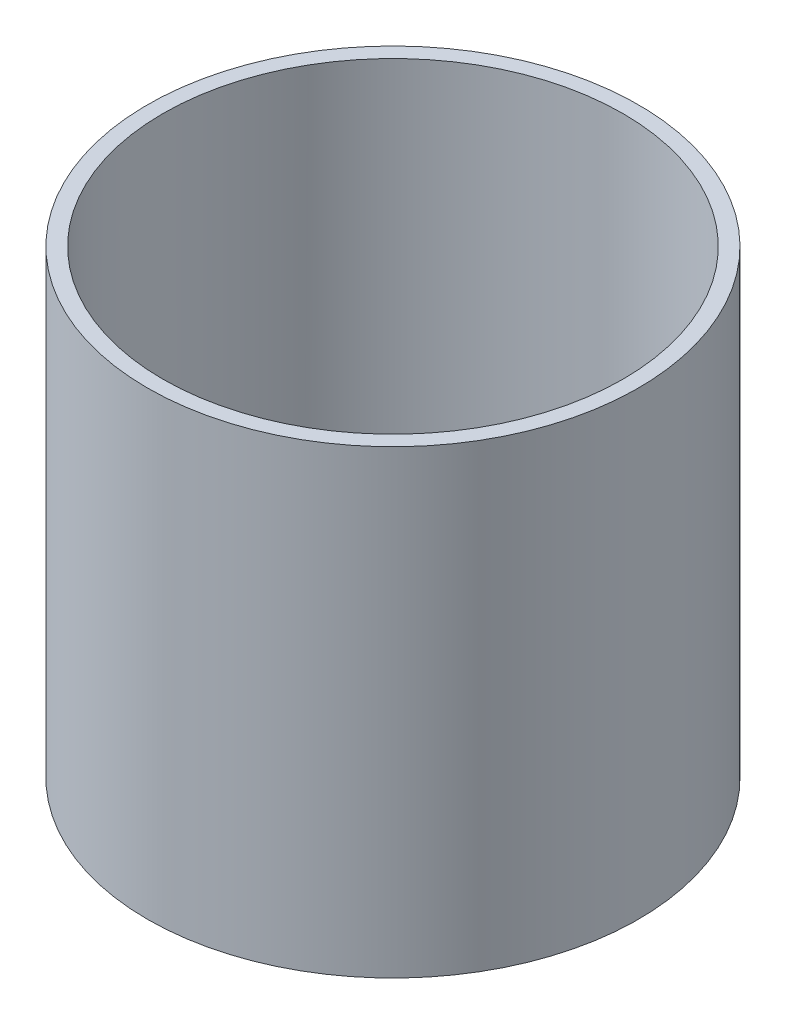
SolidWorks part; units mm, degrees
ref_plane "Plan de face" through (0, 0, 0) normal (0, 0, 1) x (1, 0, 0)
ref_plane "Plan de dessus" through (0, 0, 0) normal (0, 1, 0) x (1, 0, 0)
ref_plane "Plan de droite" through (0, 0, 0) normal (1, 0, 0) x (0, 0, -1)
sketch "Esquisse2" plane through (0, 0, 0) normal (0, 1, 0) x (1, 0, 0)
  circle A0 centre (0, 0) radius 30
  circle A1 centre (0, 0) radius 32
  dimension "D1" = 60
  dimension "D2" = 2
extrude "Boss.-Extru.2" add sketch "Esquisse2" along normal blind 60
sketch "Esquisse3" plane through (0, 0, 0) normal (0, -1, 0) x (1, 0, 0)
  circle A0 centre (0, 0) radius 32
  circle A1 centre (0, 0) radius 32 construction
extrude "Boss.-Extru.3" add sketch "Esquisse3" against normal blind 1
fillet "Congé1" radius 10 1 edges at (0, 1, -30)
